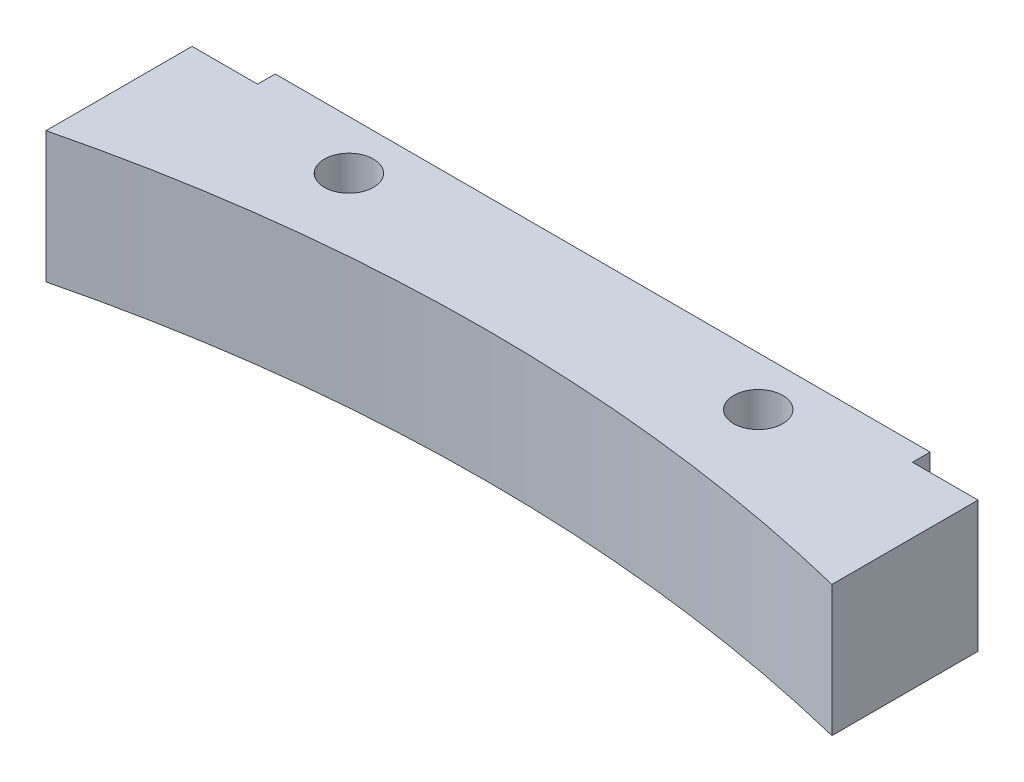
SolidWorks part; units mm, degrees
material "6061-T6 (SS)"
ref_plane "Front Plane" through (0, 0, 0) normal (0, 0, 1) x (1, 0, 0)
ref_plane "Top Plane" through (0, 0, 0) normal (0, 1, 0) x (1, 0, 0)
ref_plane "Right Plane" through (0, 0, 0) normal (1, 0, 0) x (0, 0, -1)
sketch "Sketch1" plane through (0, 0, 0) normal (0, 1, 0) x (1, 0, 0)
  line L0 (-20, 0) -> (0, 0)
  line L1 (24, -8) -> (24, -16.9227)
  line L2 (-24, -8) -> (-24, -16.9227)
  line L3 (-24, -14) -> (24, -14) construction
  line L4 (-20, 0) -> (-20, -8)
  line L5 (-20, -8) -> (-24, -8)
  line L6 (20, 0) -> (20, -8)
  line L7 (20, -8) -> (24, -8)
  line L22 (0, 0) -> (20, 0)
  line L25 (-24, -16.9227) -> (0, -114) construction
  line L26 (0, -114) -> (24, -16.9227) construction
  arc A0 (-24, -16.9227) -> (24, -16.9227) centre (0, -114) cw
  dimension "D1" = 6
  dimension "D2" = 100
  dimension "D3" = 8
  dimension "D4" = 20
  dimension "D5" = 48
extrude "Boss-Extrude1" add sketch "Sketch1" along normal mid plane 8
sketch "Sketch10" plane through (0, 4, 0) normal (0, 1, 0) x (1, 0, 0)
  line L0 (-20, -9.9227) -> (20, -9.9227) construction
  line L3 (-26.6292, -6.9227) -> (25.3174, -6.9227) construction
  line L4 (-26.6292, -14) -> (25.3174, -14) construction
  line L5 (0, 0) -> (0, -20.7484) construction
  line L6 (-20, 0) -> (-20, -8) construction
  line L7 (20, -8) -> (20, 0) construction
  line L8 (24, -16.9227) -> (24, -8) construction
  line L9 (-24, -8) -> (24, -8)
  line L10 (-24, -8) -> (-24, -6.9227)
  line L11 (-24, -6.9227) -> (24, -6.9227)
  line L12 (24, -8) -> (24, -6.9227)
  line L13 (20, 0) -> (-20, 0) construction
  line L14 (-24, -6.9227) -> (24, -6.9227)
  line L15 (-24, -6.9227) -> (-24, 0)
  line L16 (-24, 0) -> (24, 0)
  line L17 (24, -6.9227) -> (24, 0)
  circle A0 centre (-12.5, -9.9227) radius 1.5
  circle A1 centre (12.5, -9.9227) radius 1.5
  arc A2 (24, -16.9227) -> (-24, -16.9227) centre (0, -114) ccw construction
  line M14 (20, 0) -> (-20, 0)
  line M15 (-20, 0) -> (-20, -8)
  line M17 (20, -8) -> (20, 0)
  dimension "D1" = 3
  dimension "D2" = 12.5
  dimension "D4" = 10
  dimension "D5" = 3
extrude "Cut-Extrude2" cut sketch "Sketch10" against normal through all contours A0 | A1 | L11 M15 M17 M14
